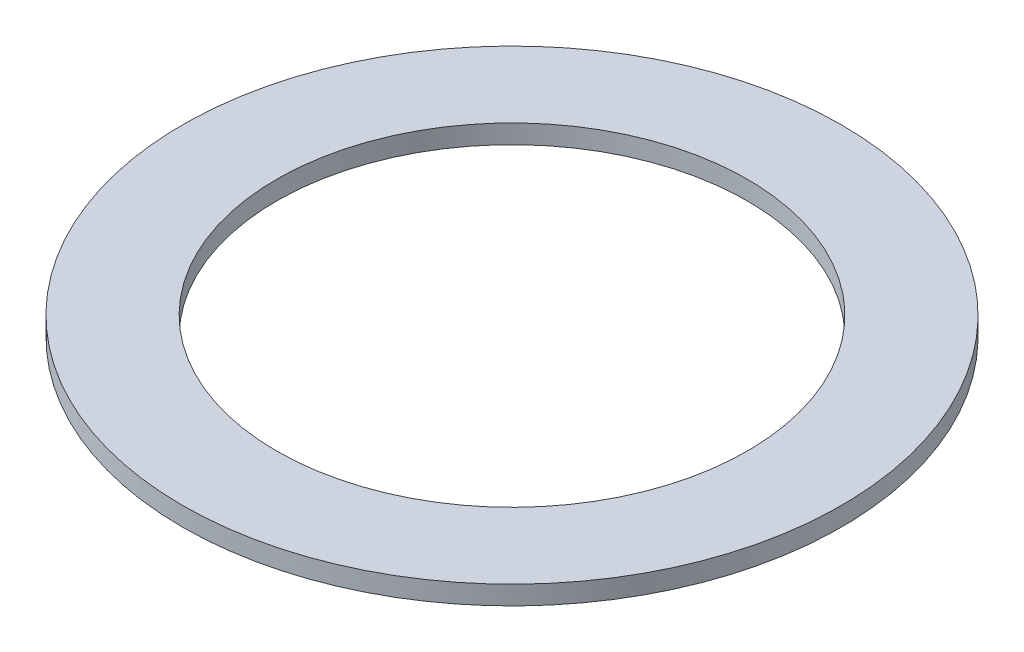
SolidWorks part; units mm, degrees
material "1.0406 (C25)"
ref_plane "Płaszczyzna przednia" through (0, 0, 0) normal (0, 0, 1) x (1, 0, 0)
ref_plane "Płaszczyzna górna" through (0, 0, 0) normal (0, 1, 0) x (1, 0, 0)
ref_plane "Płaszczyzna prawa" through (0, 0, 0) normal (1, 0, 0) x (0, 0, -1)
sketch "Szkic1" plane through (0, 0, 0) normal (0, 1, 0) x (1, 0, 0)
  circle A0 centre (0, 0) radius 17.5
  circle A1 centre (0, 0) radius 12.5
  dimension "D1" = 35
  dimension "D2" = 25
extrude "Dodanie-wyciągnięcie1" add sketch "Szkic1" along normal blind 1
